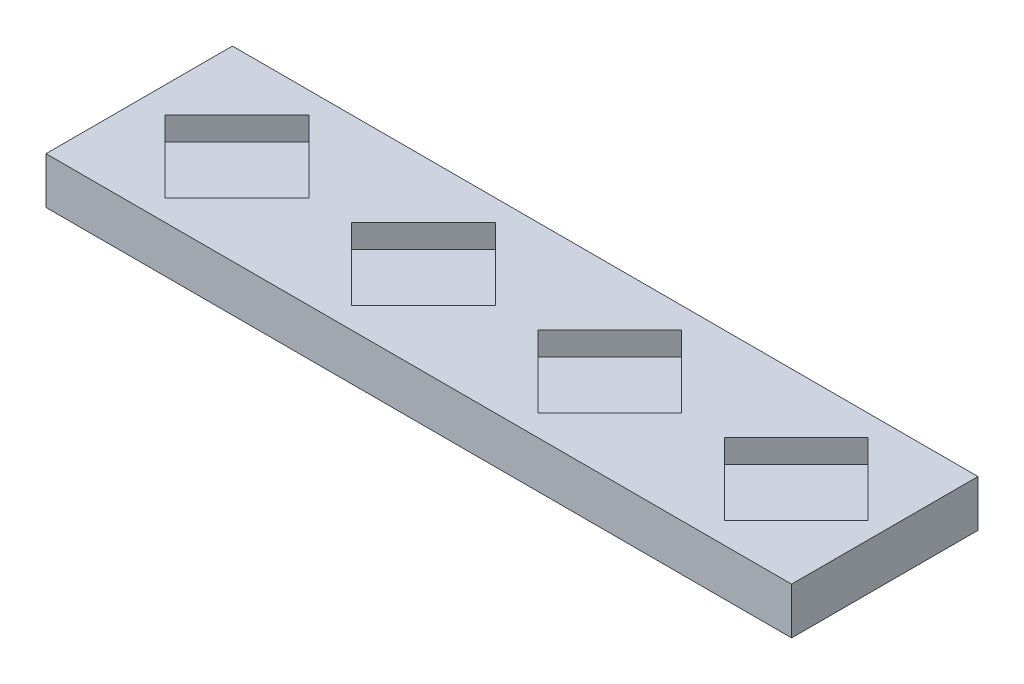
SolidWorks part; units mm, degrees
ref_plane "Front Plane" through (0, 0, 0) normal (0, 0, 1) x (1, 0, 0)
ref_plane "Top Plane" through (0, 0, 0) normal (0, 1, 0) x (1, 0, 0)
ref_plane "Right Plane" through (0, 0, 0) normal (1, 0, 0) x (0, 0, -1)
sketch "Sketch1" plane through (0, 0, 0) normal (0, 1, 0) x (1, 0, 0)
  line L0 (-203.2, 0) -> (-203.2, 50.8)
  line L1 (-203.2, 50.8) -> (0, 50.8)
  line L2 (0, 50.8) -> (0, 0)
  line L3 (0, 0) -> (-203.2, 0)
  dimension "D1" = 203.2
  dimension "D2" = 50.8
extrude "Boss-Extrude1" add sketch "Sketch1" along normal blind 12.7
sketch "Sketch2" plane through (0, 12.7, 0) normal (0, 1, 0) x (1, 0, 0)
  line L0 (-176.5347, 5.8252) -> (-156.9599, 25.4)
  line L2 (-196.1095, 25.4) -> (-176.5347, 44.9748)
  line L3 (-176.5347, 44.9748) -> (-156.9599, 25.4)
  line L5 (-196.1095, 25.4) -> (-176.5347, 5.8252)
  line L21 (-125.7347, 5.8252) -> (-106.1599, 25.4)
  line L22 (-125.7347, 44.9748) -> (-106.1599, 25.4)
  line L23 (-145.3095, 25.4) -> (-125.7347, 44.9748)
  line L24 (-145.3095, 25.4) -> (-125.7347, 5.8252)
  line L25 (-74.9347, 5.8252) -> (-55.3599, 25.4)
  line L26 (-74.9347, 44.9748) -> (-55.3599, 25.4)
  line L27 (-94.5095, 25.4) -> (-74.9347, 44.9748)
  line L28 (-94.5095, 25.4) -> (-74.9347, 5.8252)
  line L29 (-24.1347, 5.8252) -> (-4.5599, 25.4)
  line L30 (-24.1347, 44.9748) -> (-4.5599, 25.4)
  line L31 (-43.7095, 25.4) -> (-24.1347, 44.9748)
  line L32 (-43.7095, 25.4) -> (-24.1347, 5.8252)
  dimension "D1" = 4
extrude "Cut-Extrude6" cut sketch "Sketch2" against normal blind 6.35
